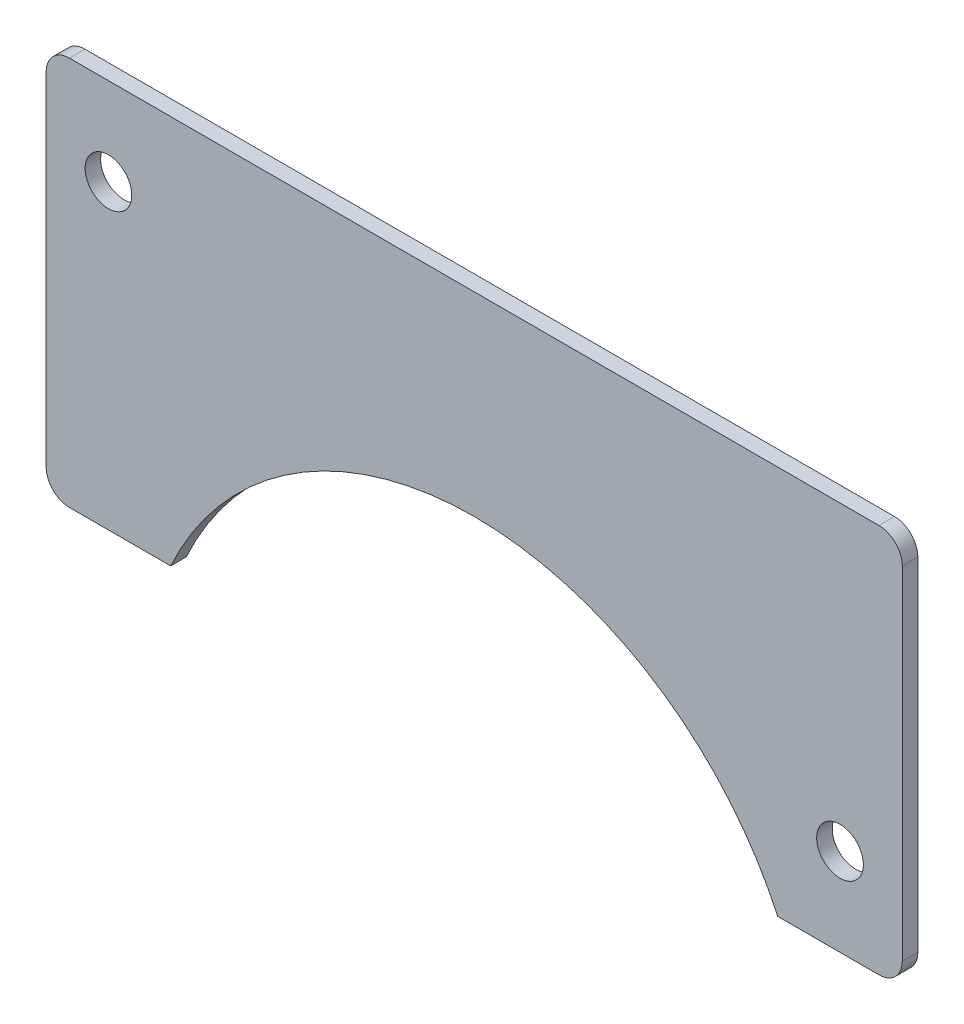
SolidWorks part; units mm, degrees
material "AISI 1035 Çelik (SS)"
ref_plane "Ön Düzlem" through (0, 0, 0) normal (0, 0, 1) x (1, 0, 0)
ref_plane "Üst Düzlem" through (0, 0, 0) normal (0, 1, 0) x (1, 0, 0)
ref_plane "Sağ Düzlem" through (0, 0, 0) normal (1, 0, 0) x (0, 0, -1)
sketch "Çizim1" plane through (0, 0, 0) normal (0, 0, 1) x (1, 0, 0)
  line L1 (-30, 0) -> (-1070, 0)
  line L2 (0, 30) -> (0, 470)
  line L3 (-30, 500) -> (-1070, 500)
  line L4 (-1100, 30) -> (-1100, 470)
  circle A0 centre (-1020, 387.5) radius 30
  circle A1 centre (-80, 112.5) radius 30
  arc A2 (-1070, 500) -> (-1100, 470) centre (-1070, 470) ccw
  arc A3 (-1070, 0) -> (-1100, 30) centre (-1070, 30) cw
  arc A4 (-30, 0) -> (0, 30) centre (-30, 30) ccw
  arc A5 (0, 470) -> (-30, 500) centre (-30, 470) ccw
  point P11 (-1100, 500)
  point P14 (-1100, 0)
  point P17 (0, 0)
  point P20 (0, 500)
  dimension "D3" = 60
  dimension "D4" = 60
  dimension "D9" = 30
  dimension "D1" = 1100
  dimension "D2" = 500
  dimension "D5" = 80
  dimension "D6" = 80
  dimension "D7" = 275
  dimension "D8" = 112.5
extrude "Yükseklik-Ekstrüzyon1" add sketch "Çizim1" along normal blind 20
sketch "Çizim2" plane through (0, 0, 0) normal (0, 0, -1) x (-1, 0, 0)
  line L0 (1070, 0) -> (30, 0) construction
  line L1 (940, 0) -> (160, 0)
  line L2 (550, 0) -> (550, 250) construction
  line L4 (80, 112.5) -> (160, 112.5) construction
  line L6 (1100, 112.5) -> (940, 112.5) construction
  line L7 (1100, 470) -> (1100, 30) construction
  line L8 (160, 112.5) -> (160, 0) construction
  line L9 (940, 112.5) -> (940, 0) construction
  arc A0 (160, 0) -> (940, 0) centre (550, -179.2) cw
  dimension "D1" = 250
  dimension "D2" = 80
  dimension "D3" = 160
extrude "Kes-Ekstrüzyon1" cut sketch "Çizim2" against normal blind 20
